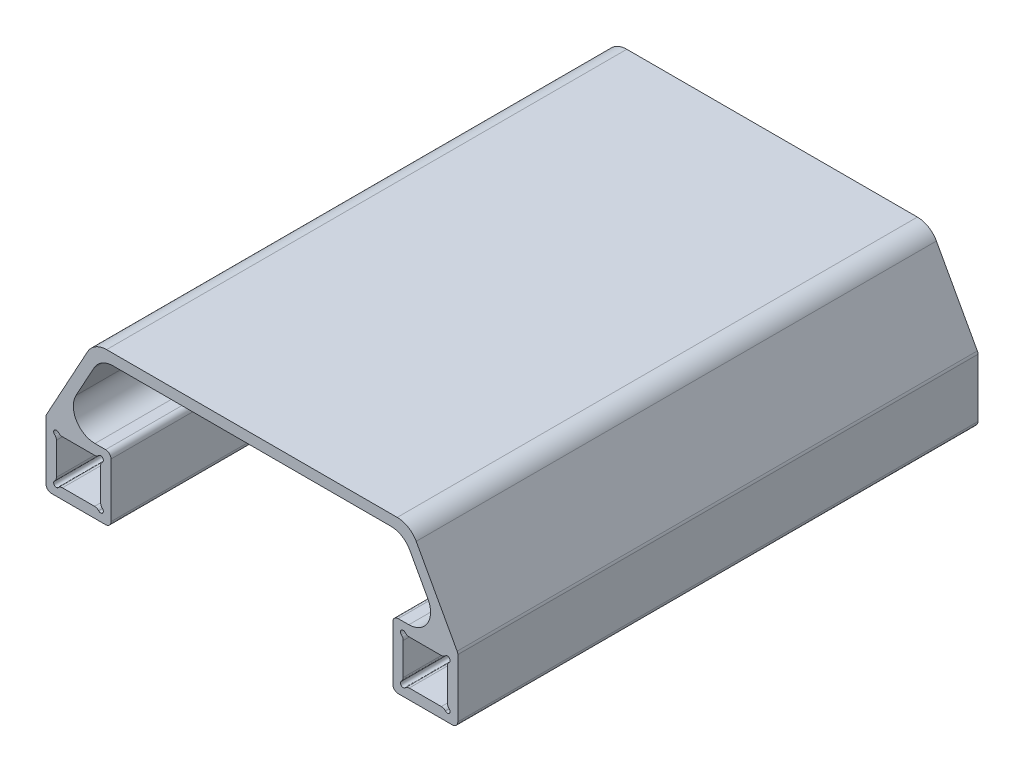
SolidWorks part; units mm, degrees
ref_plane "Front Plane" through (0, 0, 0) normal (0, 0, 1) x (1, 0, 0)
ref_plane "Top Plane" through (0, 0, 0) normal (0, 1, 0) x (1, 0, 0)
ref_plane "Right Plane" through (0, 0, 0) normal (1, 0, 0) x (0, 0, -1)
sketch "Sketch1" plane through (0, 0, 0) normal (0, 0, 1) x (1, 0, 0)
  line L1 (-8.001, 1.524) -> (-1.524, 1.524)
  line L2 (-8.001, 1.524) -> (-8.001, 8.001)
  line L3 (-8.001, 8.001) -> (-1.524, 8.001)
  line L4 (-1.524, 1.524) -> (-1.524, 8.001)
  line L5 (-8.001, 1.524) -> (-1.524, 8.001) construction
  line L6 (-8.001, 8.001) -> (-1.524, 1.524) construction
  line L7 (-9.525, 0) -> (0, 0)
  line L8 (-9.525, 0) -> (-9.525, 9.525)
  line L9 (-7.7146, 9.525) -> (0, 9.525)
  line L10 (0, 0) -> (0, 9.525)
  line L11 (-9.525, 0) -> (-38.7726, -29.2476) construction
  line L12 (-9.525, 9.525) -> (0, 0) construction
  line L13 (50.8, 0) -> (41.275, 0)
  line L14 (50.8, 0) -> (50.8, 9.525)
  line L15 (48.9896, 9.525) -> (41.275, 9.525)
  line L16 (41.275, 0) -> (41.275, 9.525)
  line L17 (50.8, 0) -> (41.275, 9.525) construction
  line L18 (50.8, 9.525) -> (41.275, 0) construction
  line L19 (49.276, 1.524) -> (42.799, 1.524)
  line L20 (49.276, 1.524) -> (49.276, 8.001)
  line L21 (49.276, 8.001) -> (42.799, 8.001)
  line L22 (42.799, 1.524) -> (42.799, 8.001)
  line L23 (49.276, 1.524) -> (42.799, 8.001) construction
  line L24 (49.276, 8.001) -> (42.799, 1.524) construction
  line L25 (-2.5276, 22.2885) -> (43.8026, 22.2885)
  line L28 (42.8625, 20.701) -> (-1.5875, 20.701)
  line L30 (42.8625, 20.701) -> (44.2545, 21.4642) construction
  line L31 (42.8625, 20.701) -> (42.8625, 22.2885) construction
  line L32 (-1.5875, 20.701) -> (-2.9795, 21.4642) construction
  line L33 (-2.5276, 22.2885) -> (-9.525, 9.525)
  line L34 (-1.5875, 20.701) -> (-7.7146, 9.525)
  line L35 (43.8026, 22.2885) -> (50.8, 9.525)
  line L36 (42.8625, 20.701) -> (48.9896, 9.525)
  point P0 (41.0958, 0)
  point P4 (-4.7625, 4.7625)
  point P11 (-4.7625, 4.7625)
  point P16 (46.0375, 4.7625)
  point P19 (46.0375, 4.7625)
  dimension "D4" = 1.5875
  dimension "D1" = 9.525
  dimension "D2" = 6.477
  dimension "D3" = 50.8
  dimension "D6" = 12.7
  dimension "D7" = 44.45
extrude "Boss-Extrude1" add sketch "Sketch1" along normal blind 76.2
fillet "Fillet1" radius 3.175 6 edges at (-2.5276, 22.2885, 38.1) (-1.5875, 20.701, 38.1) (42.8625, 20.701, 38.1) (43.8026, 22.2885, 38.1) (48.9896, 9.525, 38.1) (-7.7146, 9.525, 38.1)
fillet "Fillet2" radius 0.7937 8 edges at (41.275, 0, 38.1) (41.275, 9.525, 38.1) (50.8, 9.525, 38.1) (50.8, 0, 38.1) (0, 0, 38.1) (0, 9.525, 38.1) (-9.525, 9.525, 38.1) (-9.525, 0, 38.1)
sketch "Sketch2" plane through (0, 0, 76.2) normal (0, 0, 1) x (1, 0, 0)
  circle A0 centre (-8.001, 8.001) radius 0.3969
  circle A1 centre (-1.524, 8.001) radius 0.3969
  circle A2 centre (-1.524, 1.524) radius 0.3969
  circle A3 centre (-8.001, 1.524) radius 0.3969
  circle A4 centre (42.799, 8.001) radius 0.3969
  circle A5 centre (42.799, 1.524) radius 0.3969
  circle A6 centre (49.276, 1.524) radius 0.3969
  circle A7 centre (49.276, 8.001) radius 0.3969
  dimension "D1" = 0.7937
extrude "Cut-Extrude1" cut sketch "Sketch2" against normal through all
fillet "Fillet3" radius 0.7937 16 edges at (49.276, 7.6041, 38.1) (48.8791, 8.001, 38.1) (49.276, 1.9209, 38.1) (48.8791, 1.524, 38.1) (43.1959, 1.524, 38.1) (42.799, 1.9209, 38.1) (42.799, 7.6041, 38.1) (43.1959, 8.001, 38.1) (-7.6041, 8.001, 38.1) (-8.001, 7.6041, 38.1) (-8.001, 1.9209, 38.1) (-7.6041, 1.524, 38.1) (-1.9209, 1.524, 38.1) (-1.524, 1.9209, 38.1) (-1.524, 7.6041, 38.1) (-1.9209, 8.001, 38.1)
